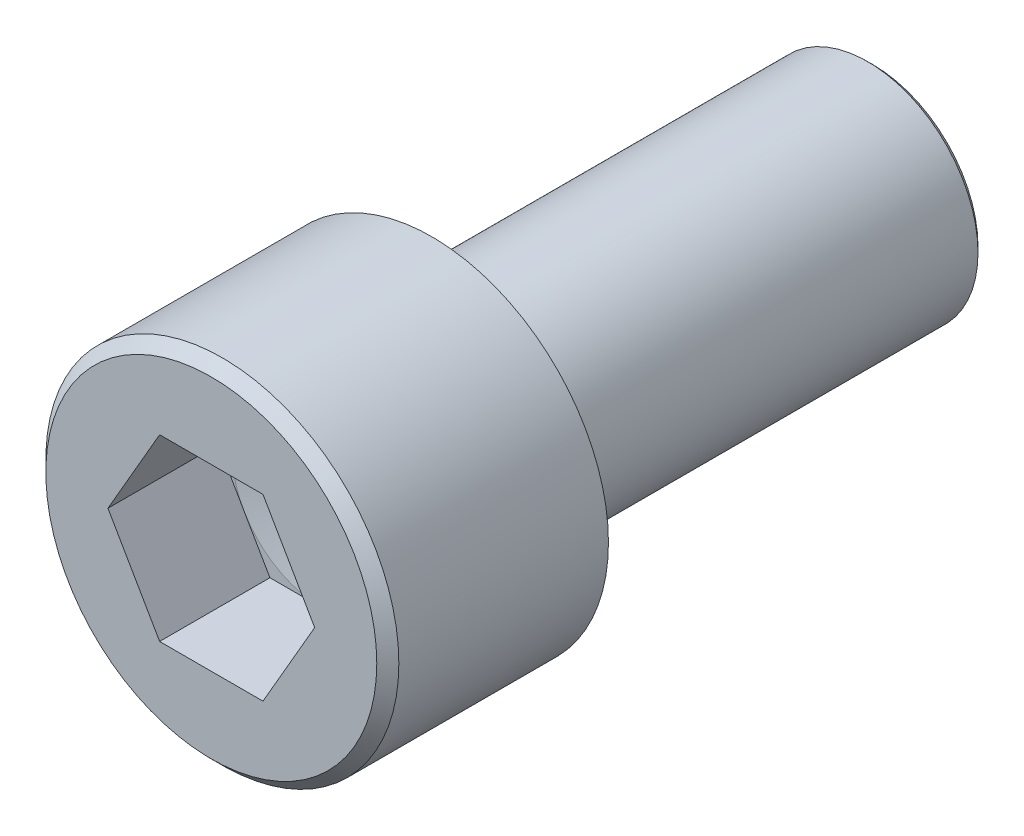
SolidWorks part; units mm, degrees
ref_plane "Front Plane" through (0, 0, 0) normal (0, 0, 1) x (1, 0, 0)
ref_plane "Top Plane" through (0, 0, 0) normal (0, 1, 0) x (1, 0, 0)
ref_plane "Right Plane" through (0, 0, 0) normal (1, 0, 0) x (0, 0, -1)
sketch "Çizim1" plane through (0, 0, 0) normal (0, 0, 1) x (1, 0, 0)
  circle A0 centre (0, 0) radius 8
  dimension "KAFA_CAPI" = 16
extrude "KAFA_YUKSEKLIGI" add sketch "Çizim1" along normal blind 10 contours A0
chamfer "Pah1" distance 0.5 angle 45 1 edges at (8, 0, 10)
sketch "Çizim2" plane through (0, 0, 10) normal (0, 0, 1) x (1, 0, 0)
  line L1 (-4.685, 0) -> (-2.3425, -4.0573)
  line L2 (-2.3425, -4.0573) -> (2.3425, -4.0573)
  line L3 (2.3425, -4.0573) -> (4.685, 0)
  line L4 (4.685, 0) -> (2.3425, 4.0573)
  line L5 (2.3425, 4.0573) -> (-2.3425, 4.0573)
  line L6 (-2.3425, 4.0573) -> (-4.685, 0)
  circle A1 centre (0, 0) radius 4.685 construction
  dimension "ALTIGEN ÇAP" = 9.37
extrude "ALTIGEN_BOSALTMA" cut sketch "Çizim2" against normal blind 5
sketch "Çizim4" plane through (0, 0, 5) normal (0, 0, 1) x (1, 0, 0)
  line L0 (-2.3425, -4.0573) -> (2.3425, -4.0573) construction
  line L1 (-2.3425, 4.0573) -> (-4.685, 0) construction
  line L2 (4.685, 0) -> (2.3425, 4.0573) construction
  circle A0 centre (0, 0) radius 4.0573
extrude "Kes-Ekstrüzyon2" cut sketch "Çizim4" against normal blind 0.9 draft 80
sketch "Çizim5" plane through (0, 0, 0) normal (0, 1, 0) x (1, 0, 0)
  line L0 (0, 0) -> (0, 20)
  line L1 (5, 0) -> (5, 20)
  line L2 (0, 20) -> (5, 20)
  line L3 (0, 0) -> (5, 0)
  point P4 (5, 20)
  dimension "diş yüksekliği" = 20
  dimension "diş çapı" = 5
revolve "Döndür1" add sketch "Çizim5" angle 360 about L0
fillet "Radyus1" radius 0.25 1 edges at (5, 0, 0)
chamfer "Pah2" distance 0.25 angle 45 1 edges at (5, 0, -20)
